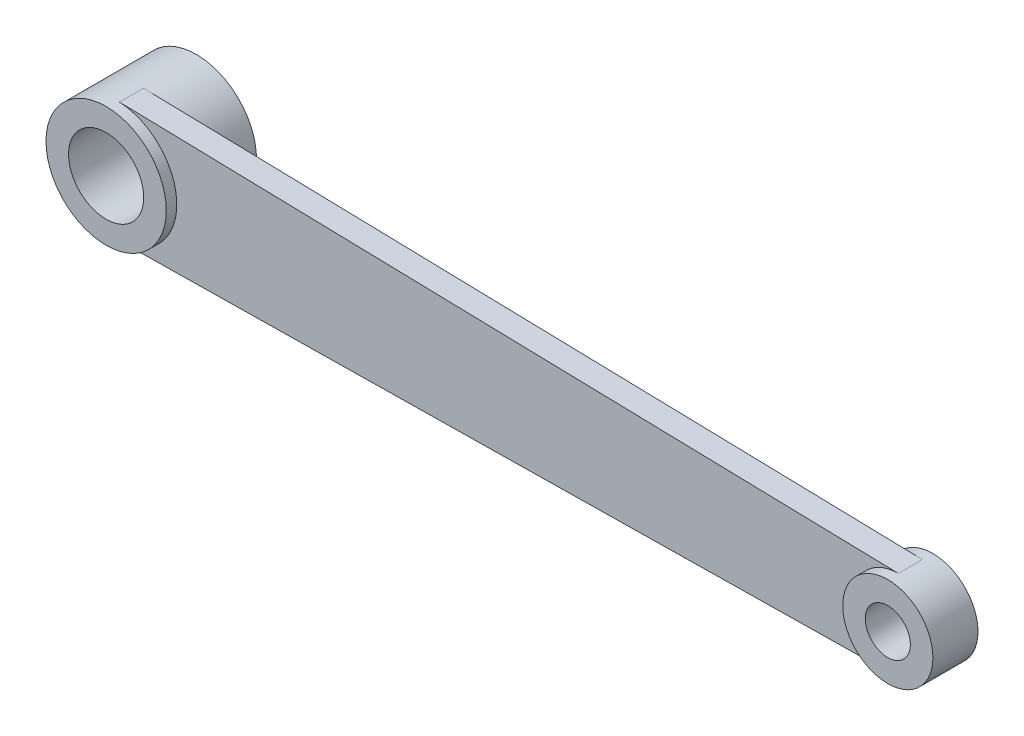
SolidWorks part; units mm, degrees
material "Cast Alloy Steel"
ref_plane "Front Plane" through (0, 0, 0) normal (0, 0, 1) x (1, 0, 0)
ref_plane "Top Plane" through (0, 0, 0) normal (0, 1, 0) x (1, 0, 0)
ref_plane "Right Plane" through (0, 0, 0) normal (1, 0, 0) x (0, 0, -1)
sketch "Sketch1" plane through (0, 0, 0) normal (0, 0, 1) x (1, 0, 0)
  line L0 (-200.1851, 20) -> (59.8149, 13.7273)
  line L1 (-200.1851, -20) -> (59.8149, -16.2727)
  circle A0 centre (-200.1851, 0) radius 20
  circle A1 centre (59.8149, -1.2727) radius 15
  dimension "D1" = 40
  dimension "D2" = 30
  dimension "D3" = 260
extrude "Boss-Extrude1" add sketch "Sketch1" along normal mid plane 8 contours A1 L0 A0 L1
ref_plane "Plane1" through (0, 0, 0) normal (0, 0, 1) x (1, 0, 0)
sketch "Sketch2" plane through (0, 0, 0) normal (0, 0, 1) x (1, 0, 0)
  circle A0 centre (-200.1851, 0) radius 20
  circle A1 centre (-200.1851, 0) radius 12.5
  circle A2 centre (59.8149, -1.2727) radius 15
  circle A3 centre (59.8149, -1.2727) radius 7.5
  dimension "D1" = 40
  dimension "D2" = 25
  dimension "D3" = 15
extrude "Boss-Extrude2" add sketch "Sketch2" along normal mid plane 15
sketch "Sketch3" plane through (0, 0, -7.5) normal (0, 0, -1) x (-1, 0, 0)
  circle A0 centre (200.1851, 0) radius 12.5
  circle A1 centre (200.1851, 0) radius 20
  dimension "D1" = 40
  dimension "D2" = 25
extrude "Boss-Extrude3" add sketch "Sketch3" along normal blind 15 contours A1 | A0
